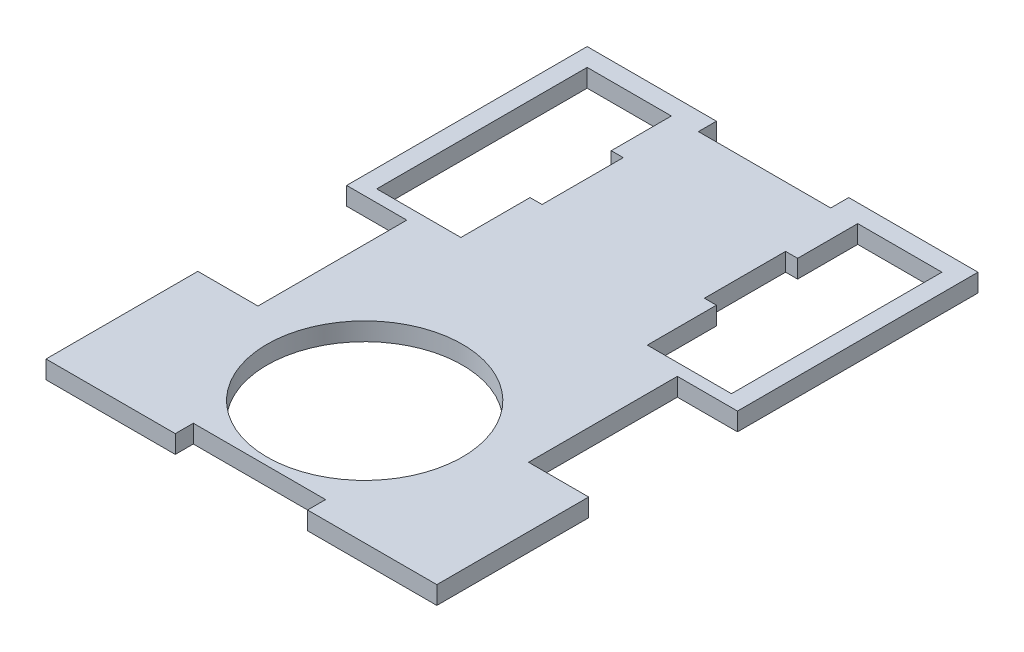
SolidWorks part; units mm, degrees
ref_plane "Front" through (0, 0, 0) normal (0, 0, 1) x (1, 0, 0)
ref_plane "Top" through (0, 0, 0) normal (0, 1, 0) x (1, 0, 0)
ref_plane "Right" through (0, 0, 0) normal (1, 0, 0) x (0, 0, -1)
sketch "Sketch1" plane through (0, 0, 0) normal (0, 1, 0) x (1, 0, 0)
  line L1 (0, 0) -> (130, 0)
  line L2 (0, 0) -> (0, 180)
  line L3 (0, 180) -> (130, 180)
  line L4 (130, 0) -> (130, 180)
  dimension "D1" = 130
  dimension "D2" = 180
extrude "Boss-Extrude1" add sketch "Sketch1" along normal blind 6
sketch "Sketch2" plane through (0, 6, 0) normal (0, 1, 0) x (1, 0, 0)
  line L0 (0, 0) -> (130, 0) construction
  line L1 (0, 180) -> (0, 0) construction
  line L2 (130, 180) -> (0, 180) construction
  line L3 (6, 174) -> (34, 174)
  line L4 (6, 174) -> (6, 104)
  line L5 (6, 104) -> (34, 104)
  line L6 (34, 174) -> (34, 104)
  line L7 (130, 0) -> (130, 180) construction
  line L8 (124, 174) -> (96, 174)
  line L9 (124, 174) -> (124, 104)
  line L10 (124, 104) -> (96, 104)
  line L11 (96, 174) -> (96, 104)
  circle A0 centre (65, 41) radius 32.5
  dimension "D2" = 65
  dimension "D1" = 41
  dimension "D3" = 65
  dimension "D4" = 28
  dimension "D5" = 70
  dimension "D6" = 6
  dimension "D7" = 6
  dimension "D8" = 28
  dimension "D9" = 70
  dimension "D10" = 6
  dimension "D11" = 6
extrude "Cut-Extrude2" cut sketch "Sketch2" against normal blind 6
sketch "Sketch3" plane through (0, 6, 0) normal (0, 1, 0) x (1, 0, 0)
  line L0 (130, 0) -> (130, 180) construction
  line L1 (130, 100) -> (110, 100)
  line L2 (130, 100) -> (130, 50.5)
  line L3 (130, 50.5) -> (110, 50.5)
  line L4 (110, 100) -> (110, 50.5)
  line L5 (130, 180) -> (0, 180) construction
  line L6 (0, 180) -> (0, 0) construction
  line L7 (0, 100) -> (20, 100)
  line L8 (0, 100) -> (0, 50.5)
  line L9 (0, 50.5) -> (20, 50.5)
  line L10 (20, 100) -> (20, 50.5)
  dimension "D1" = 49.5
  dimension "D2" = 80
  dimension "D3" = 80
  dimension "D4" = 20
extrude "Cut-Extrude3" cut sketch "Sketch3" against normal through all
sketch "Sketch4" plane through (0, 6, 0) normal (0, 1, 0) x (1, 0, 0)
  line L0 (130, 180) -> (0, 180) construction
  line L1 (43, 180) -> (87, 180)
  line L2 (43, 180) -> (43, 174)
  line L3 (43, 174) -> (87, 174)
  line L4 (87, 180) -> (87, 174)
  line L5 (130, 100) -> (130, 180) construction
  line L7 (0, 0) -> (130, 0) construction
  line L8 (87, 0) -> (43, 0)
  line L9 (87, 0) -> (87, 6)
  line L10 (87, 6) -> (43, 6)
  line L11 (43, 0) -> (43, 6)
  line L12 (130, 0) -> (130, 50.5) construction
  line L13 (0, 180) -> (0, 100) construction
  line L14 (34, 180) -> (38, 180)
  line L15 (34, 180) -> (34, 154)
  line L16 (34, 154) -> (38, 154)
  line L17 (38, 180) -> (38, 154)
  line L18 (34, 154) -> (38, 154)
  line L19 (34, 154) -> (34, 127)
  line L20 (34, 127) -> (38, 127)
  line L21 (38, 154) -> (38, 127)
  line L22 (96, 180) -> (92, 180)
  line L23 (96, 180) -> (96, 154)
  line L24 (96, 154) -> (92, 154)
  line L25 (92, 180) -> (92, 154)
  line L26 (96, 154) -> (92, 154)
  line L27 (96, 154) -> (96, 127)
  line L28 (96, 127) -> (92, 127)
  line L29 (92, 154) -> (92, 127)
  line M11 (34, 174) -> (34, 104)
  line M21 (130, 180) -> (0, 180)
  line M27 (0, 0) -> (130, 0)
  dimension "D1" = 44
  dimension "D2" = 6
  dimension "D3" = 43
  dimension "D4" = 6
  dimension "D5" = 44
  dimension "D6" = 43
  dimension "D7" = 26
  dimension "D8" = 27
  dimension "D9" = 4
  dimension "D10" = 34
  dimension "D11" = 34
extrude "Cut-Extrude4" cut sketch "Sketch4" against normal through all contours L4 L2 L3 M21 | L21 L16 L20 M11 | L24 L29 L28 L27 | L11 L9 L10 M27
